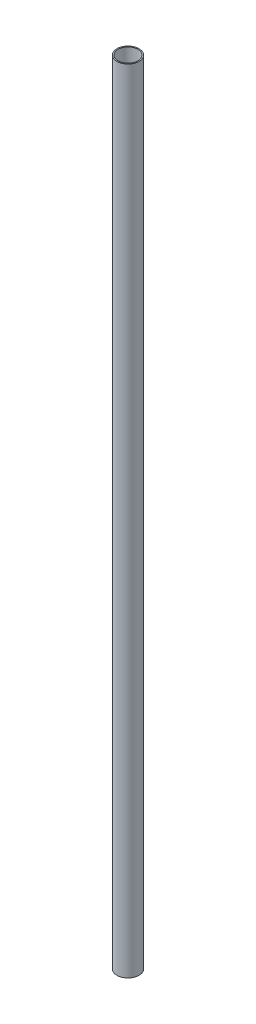
SolidWorks part; units mm, degrees
ref_plane "Front Plane" through (0, 0, 0) normal (0, 0, 1) x (1, 0, 0)
ref_plane "Top Plane" through (0, 0, 0) normal (0, 1, 0) x (1, 0, 0)
ref_plane "Right Plane" through (0, 0, 0) normal (1, 0, 0) x (0, 0, -1)
sketch "Sketch1" plane through (0, 0, 0) normal (0, 1, 0) x (1, 0, 0)
  circle A0 centre (0, 0) radius 11
  circle A1 centre (0, 0) radius 9.9
  dimension "D1" = 22
  dimension "D2" = 19.8
extrude "Boss-Extrude1" add sketch "Sketch1" along normal blind 786.6
